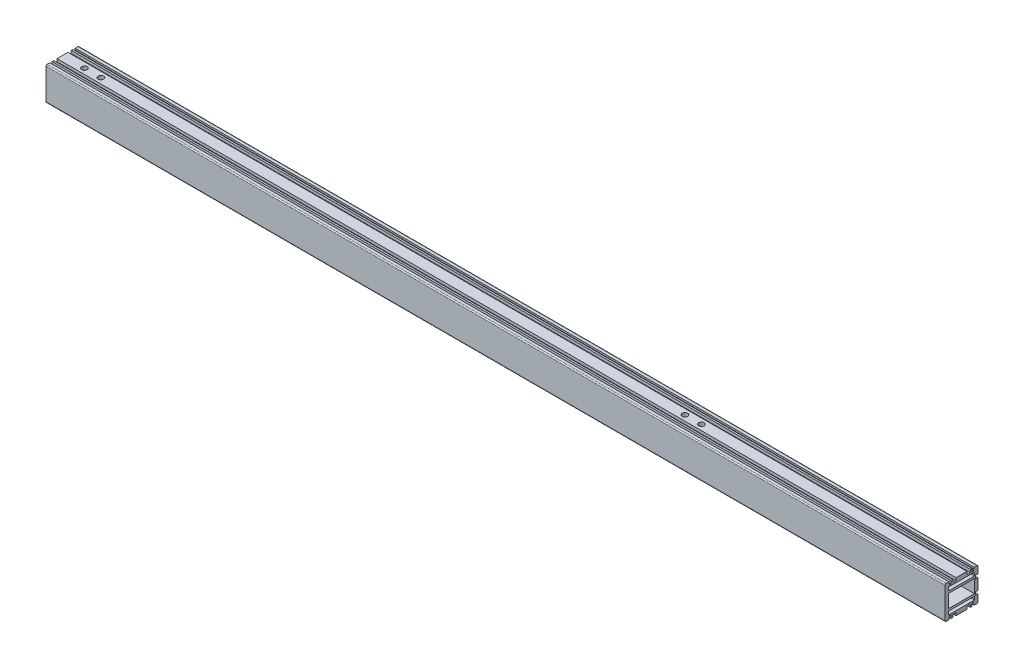
SolidWorks part; units mm, degrees
ref_plane "前视基准面" through (0, 0, 0) normal (0, 0, 1) x (1, 0, 0)
ref_plane "上视基准面" through (0, 0, 0) normal (0, 1, 0) x (1, 0, 0)
ref_plane "右视基准面" through (0, 0, 0) normal (1, 0, 0) x (0, 0, -1)
sketch "草图1" plane through (0, 0, 0) normal (1, 0, 0) x (0, 0, -1)
  line L0 (-15, 15) -> (15, -15) construction
  line L1 (-14, 15) -> (-11.5, 15)
  line L2 (-15, 14) -> (-15, -14)
  line L3 (-14, -15) -> (-11.5, -15)
  line L4 (15, 14) -> (15, 8)
  line L5 (15, 15) -> (-15, -15) construction
  line L6 (-11.5, 15) -> (-11.5, 13.5)
  line L7 (-11.5, 13.5) -> (-11.4, 13.5)
  line L8 (-11, 13.1) -> (-11, 12)
  line L9 (-11, 12) -> (-9.5, 12)
  line L10 (-9.5, 12) -> (-9.5, 15)
  line L11 (-9.5, 15) -> (-8, 15)
  line L12 (-8, 15) -> (-8, 12.5)
  line L13 (-8, 12.5) -> (-5, 12.5)
  line L14 (-5, 12.5) -> (-5, 15)
  line L15 (-5, 15) -> (5, 15)
  line L16 (0, 21.5201) -> (0, -18.309) construction
  line L17 (0, 55) -> (0, -55) construction
  line L18 (5, 12.5) -> (5, 15)
  line L19 (8, 12.5) -> (5, 12.5)
  line L20 (8, 15) -> (8, 12.5)
  line L21 (9.5, 15) -> (8, 15)
  line L22 (9.5, 12) -> (9.5, 15)
  line L23 (11, 12) -> (9.5, 12)
  line L24 (11, 13.1) -> (11, 12)
  line L25 (11.5, 13.5) -> (11.4, 13.5)
  line L26 (11.5, 15) -> (11.5, 13.5)
  line L27 (8, 15) -> (9.5, 15)
  line L28 (11.5, 15) -> (14, 15)
  line L29 (-19.8303, 0) -> (22.13, 0) construction
  line L30 (55, 0) -> (-55, 0) construction
  line L31 (8, -15) -> (9.5, -15)
  line L32 (11.5, -15) -> (11.5, -13.5)
  line L33 (11.5, -13.5) -> (11.4, -13.5)
  line L34 (11, -13.1) -> (11, -12)
  line L35 (11, -12) -> (9.5, -12)
  line L36 (9.5, -12) -> (9.5, -15)
  line L37 (9.5, -15) -> (8, -15)
  line L38 (8, -15) -> (8, -12.5)
  line L39 (8, -12.5) -> (5, -12.5)
  line L40 (5, -12.5) -> (5, -15)
  line L41 (-5, -15) -> (5, -15)
  line L42 (-5, -12.5) -> (-5, -15)
  line L43 (-8, -12.5) -> (-5, -12.5)
  line L44 (-8, -15) -> (-8, -12.5)
  line L45 (-9.5, -15) -> (-8, -15)
  line L46 (-9.5, -12) -> (-9.5, -15)
  line L47 (-11, -12) -> (-9.5, -12)
  line L48 (-11, -13.1) -> (-11, -12)
  line L49 (-11.5, -13.5) -> (-11.4, -13.5)
  line L50 (-11.5, -15) -> (-11.5, -13.5)
  line L51 (-9.5, -15) -> (-8, -15)
  line L52 (-5, -15) -> (5, -15)
  line L53 (8, -15) -> (9.5, -15)
  line L54 (11.5, -15) -> (14, -15)
  line L55 (15, 8) -> (12.5, 8)
  line L56 (12.5, 8) -> (12.5, 5)
  line L57 (12.5, 5) -> (15, 5)
  line L58 (12.5, -5) -> (15, -5)
  line L59 (12.5, -8) -> (12.5, -5)
  line L60 (15, -8) -> (12.5, -8)
  line L61 (15, 5) -> (15, -5)
  line L62 (15, -8) -> (15, -14)
  line L63 (12, -10.5) -> (12, -8.5)
  line L64 (-11.5, 11) -> (11.5, 11)
  line L65 (-12, 10.5) -> (-12, 8.5)
  line L66 (-11.5, 8) -> (11.5, 8)
  line L67 (12, 10.5) -> (12, 8.5)
  line L68 (-11.5, -8) -> (11.5, -8)
  line L69 (-12, -10.5) -> (-12, -8.5)
  line L70 (-11.5, -11) -> (11.5, -11)
  line L72 (-11.75, 6) -> (11.75, 6)
  line L73 (-11.75, 6) -> (-11.75, -6)
  line L74 (-11.75, -6) -> (11.75, -6)
  line L75 (11.75, 6) -> (11.75, -6)
  arc A0 (12, 8.5) -> (11.5, 8) centre (11.5, 8.5) cw
  arc A1 (11.5, 11) -> (12, 10.5) centre (11.5, 10.5) cw
  arc A2 (-11.5, 11) -> (-12, 10.5) centre (-11.5, 10.5) ccw
  arc A3 (-11.5, 8) -> (-12, 8.5) centre (-11.5, 8.5) cw
  arc A4 (-11, -13.1) -> (-11.4, -13.5) centre (-11.4, -13.1) cw
  arc A5 (11.4, -13.5) -> (11, -13.1) centre (11.4, -13.1) cw
  arc A6 (11.4, 13.5) -> (11, 13.1) centre (11.4, 13.1) ccw
  arc A7 (-11, 13.1) -> (-11.4, 13.5) centre (-11.4, 13.1) ccw
  arc A8 (-11.5, -8) -> (-12, -8.5) centre (-11.5, -8.5) ccw
  arc A9 (-11.5, -11) -> (-12, -10.5) centre (-11.5, -10.5) cw
  arc A10 (11.5, -11) -> (12, -10.5) centre (11.5, -10.5) ccw
  arc A11 (12, -8.5) -> (11.5, -8) centre (11.5, -8.5) ccw
  arc A12 (14, 15) -> (15, 14) centre (14, 14) cw
  arc A13 (14, -15) -> (15, -14) centre (14, -14) ccw
  arc A14 (-15, -14) -> (-14, -15) centre (-14, -14) ccw
  arc A15 (-15, 14) -> (-14, 15) centre (-14, 14) cw
  point P69 (12, 11)
  point P72 (-12, 11)
  point P77 (-11, -13.5)
  point P80 (11, -13.5)
  point P83 (11, 13.5)
  point P86 (-11, 13.5)
  point P99 (-12, -11)
  point P100 (12, -11)
  dimension "D17" = 0.5
  dimension "D18" = 0.4
  dimension "D21" = 1
  dimension "D1" = 3.5
  dimension "D2" = 1.5
  dimension "D3" = 0.5
  dimension "D4" = 1.5
  dimension "D5" = 3
  dimension "D6" = 30
  dimension "D7" = 30
  dimension "D8" = 1.5
  dimension "D9" = 2.5
  dimension "D10" = 3
  dimension "D11" = 2.5
  dimension "D12" = 7
  dimension "D13" = 3
  dimension "D14" = 4
  dimension "D15" = 3
  dimension "D16" = 24
  dimension "D19" = 23.5
  dimension "D20" = 12
extrude "凸台-拉伸1" add sketch "草图1" along normal mid plane 819 contours A15 L2 A14 L3 L50 L49 A4 L48 L47 L46 L45 L44 L43 L42 L41 L40 L39 L38 L31 L36 L35 L34 A5 L33 L32 L54 A13 L62 L60 L59 L58 L61 L57 L56 L55 L4 A12 L28 L26 L25 A6 L24 L23 L22 L21 L20 L19 L18 L15 L14 L13
hole_wizard "M6 螺纹孔1" positions "草图3" profile "草图2" tap size "M6" standard "GB"
sketch "草图3" plane through (0, -15, 0) normal (0, -1, 0) x (1, 0, 0)
  line L0 (-409.5, 5) -> (-409.5, -5) construction
  line L1 (409.5, 15) -> (-409.5, 15) construction
  point P0 (-389.5, 0)
  point P1 (-374.5, 0)
  point P4 (192.5, 0)
  point P7 (207.5, 0)
  point P10 (277.5, 0)
  point P13 (292.5, 0)
  point P16 (374.5, 0)
  point P19 (389.5, 0)
  dimension "D1" = 20
  dimension "D2" = 15
sketch "草图2" plane through (-389.5, -15, 0) normal (1, 0, 0) x (0, 0, -1)
  line L0 (0, 0) -> (0, 16.5022)
  line L1 (0, 16.5022) -> (2.5, 15)
  line L2 (2.5, 15) -> (2.5, 0)
  line L5 (2.5, 0) -> (0, 0)
  line L10 (0, 16.5022) -> (-2.5, 15) construction
  line L11 (0, -6.35) -> (0, 107.95) construction
  dimension "螺纹孔钻头直径" = 5
  dimension "螺纹孔钻头深度" = 15
  dimension "导头角度" = 118
cosmetic thread "孔螺蚊线1" parameters "D1"=9, "D2"=6
cosmetic thread "孔螺蚊线2" parameters "D1"=9, "D2"=6
cosmetic thread "孔螺蚊线3" parameters "D1"=9, "D2"=6
cosmetic thread "孔螺蚊线4" parameters "D1"=9, "D2"=6
cosmetic thread "孔螺蚊线5" parameters "D1"=9, "D2"=6
cosmetic thread "孔螺蚊线6" parameters "D1"=9, "D2"=6
cosmetic thread "孔螺蚊线7" parameters "D1"=9, "D2"=6
cosmetic thread "孔螺蚊线8" parameters "D1"=9, "D2"=6
hole_wizard "M6 螺纹孔2" positions "草图5" profile "草图4" tap size "M6" standard "GB"
sketch "草图5" plane through (0, 15, 0) normal (0, 1, 0) x (-1, 0, 0)
  line L0 (409.5, 5) -> (409.5, -5) construction
  line L1 (-409.5, 15) -> (409.5, 15) construction
  point P0 (389.5, 0)
  point P1 (374.5, 0)
  point P4 (-157.5, 0)
  point P7 (-172.5, 0)
  dimension "D1" = 20
  dimension "D2" = 15
sketch "草图4" plane through (-389.5, 15, 0) normal (1, 0, 0) x (0, 0, 1)
  line L0 (0, 0) -> (0, 16.5022)
  line L1 (0, 16.5022) -> (2.5, 15)
  line L2 (2.5, 15) -> (2.5, 0)
  line L5 (2.5, 0) -> (0, 0)
  line L10 (0, 16.5022) -> (-2.5, 15) construction
  line L11 (0, -6.35) -> (0, 107.95) construction
  dimension "螺纹孔钻头直径" = 5
  dimension "螺纹孔钻头深度" = 15
  dimension "导头角度" = 118
cosmetic thread "孔螺蚊线9" parameters "D1"=9, "D2"=6
cosmetic thread "孔螺蚊线10" parameters "D1"=9, "D2"=6
cosmetic thread "孔螺蚊线11" parameters "D1"=9, "D2"=6
cosmetic thread "孔螺蚊线12" parameters "D1"=9, "D2"=6
hole_wizard "M6 螺纹孔3" positions "草图9" profile "草图8" tap size "M6" standard "GB"
sketch "草图9" plane through (0, 0, -15) normal (0, 0, -1) x (-1, 0, 0)
  line L0 (-227.5, 5) -> (-227.5, -5) construction
  line L1 (-409.5, 15) -> (409.5, 15) construction
  point P0 (-192.5, 0)
  point P1 (-207.5, 0)
  point P4 (-277.5, 0)
  point P7 (-292.5, 0)
  point P10 (-374.5, 0)
  point P13 (-389.5, 0)
  dimension "D1" = 35
  dimension "D2" = 15
sketch "草图8" plane through (192.5, 0, -15) normal (1, 0, 0) x (0, 1, 0)
  line L0 (0, 0) -> (0, 16.5022)
  line L1 (0, 16.5022) -> (2.5, 15)
  line L2 (2.5, 15) -> (2.5, 0)
  line L5 (2.5, 0) -> (0, 0)
  line L10 (0, 16.5022) -> (-2.5, 15) construction
  line L11 (0, -6.35) -> (0, 107.95) construction
  dimension "螺纹孔钻头直径" = 5
  dimension "螺纹孔钻头深度" = 15
  dimension "导头角度" = 118
cosmetic thread "孔螺蚊线13" parameters "D1"=3.25, "D2"=6
cosmetic thread "孔螺蚊线14" parameters "D1"=3.25, "D2"=6
cosmetic thread "孔螺蚊线15" parameters "D1"=3.25, "D2"=6
cosmetic thread "孔螺蚊线16" parameters "D1"=3.25, "D2"=6
cosmetic thread "孔螺蚊线17" parameters "D1"=3.25, "D2"=6
cosmetic thread "孔螺蚊线18" parameters "D1"=3.25, "D2"=6
